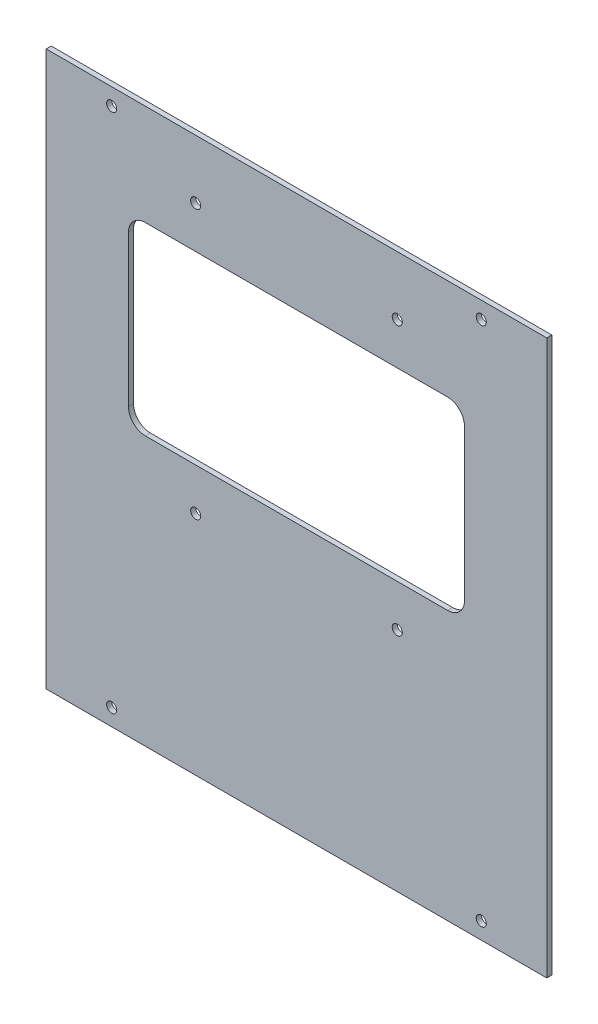
SolidWorks part; units mm, degrees
material "Alliage 1060"
ref_plane "Plan de face" through (0, 0, 0) normal (0, 0, 1) x (1, 0, 0)
ref_plane "Plan de dessus" through (0, 0, 0) normal (0, 1, 0) x (1, 0, 0)
ref_plane "Plan de droite" through (0, 0, 0) normal (1, 0, 0) x (0, 0, -1)
sketch "Esquisse1" plane through (0, 0, 0) normal (0, 0, 1) x (1, 0, 0)
  line L0 (0, 80) -> (0, 0) construction
  line L1 (-74.5, 165) -> (74.5, 165)
  line L2 (-74.5, 165) -> (-74.5, 0)
  line L3 (-74.5, 0) -> (74.5, 0)
  line L4 (74.5, 165) -> (74.5, 0)
  line L5 (-50, 135) -> (50, 135)
  line L6 (-50, 135) -> (-50, 80)
  line L7 (-50, 80) -> (50, 80)
  line L8 (50, 135) -> (50, 80)
  dimension "D1" = 165
  dimension "D2" = 149
  dimension "D3" = 55
  dimension "D4" = 100
  dimension "D5" = 80
extrude "Boss.-Extru.1" add sketch "Esquisse1" along normal blind 1.5
fillet "Congé1" radius 5 4 edges at (50, 80, 0.75) (50, 135, 0.75) (-50, 135, 0.75) (-50, 80, 0.75)
sketch "Esquisse2" plane through (0, 0, 1.5) normal (0, 0, 1) x (1, 0, 0)
  line L0 (-50, 107.5) -> (0, 107.5) construction
  line L1 (-50, 130) -> (-50, 85) construction
  line L2 (0, 107.5) -> (0, 135) construction
  line L3 (45, 135) -> (-45, 135) construction
  line L4 (-74.5, 82.5) -> (74.5, 82.5) construction
  line L5 (-74.5, 165) -> (-74.5, 0) construction
  line L6 (74.5, 0) -> (74.5, 165) construction
  line L7 (74.5, 165) -> (-74.5, 165) construction
  circle A0 centre (-30, 147.5) radius 1.5
  circle A1 centre (-30, 67.5) radius 1.5
  circle A2 centre (30, 67.5) radius 1.5
  circle A3 centre (30, 147.5) radius 1.5
  circle A4 centre (-55, 160) radius 1.5
  circle A5 centre (-55, 5) radius 1.5
  circle A6 centre (55, 5) radius 1.5
  circle A7 centre (55, 160) radius 1.5
  dimension "D1" = 80
  dimension "D2" = 3
  dimension "D3" = 60
  dimension "D4" = 5
  dimension "D5" = 110
  dimension "D6" = 155
extrude "Enlèv. mat.-Extru.1" cut sketch "Esquisse2" against normal through all
